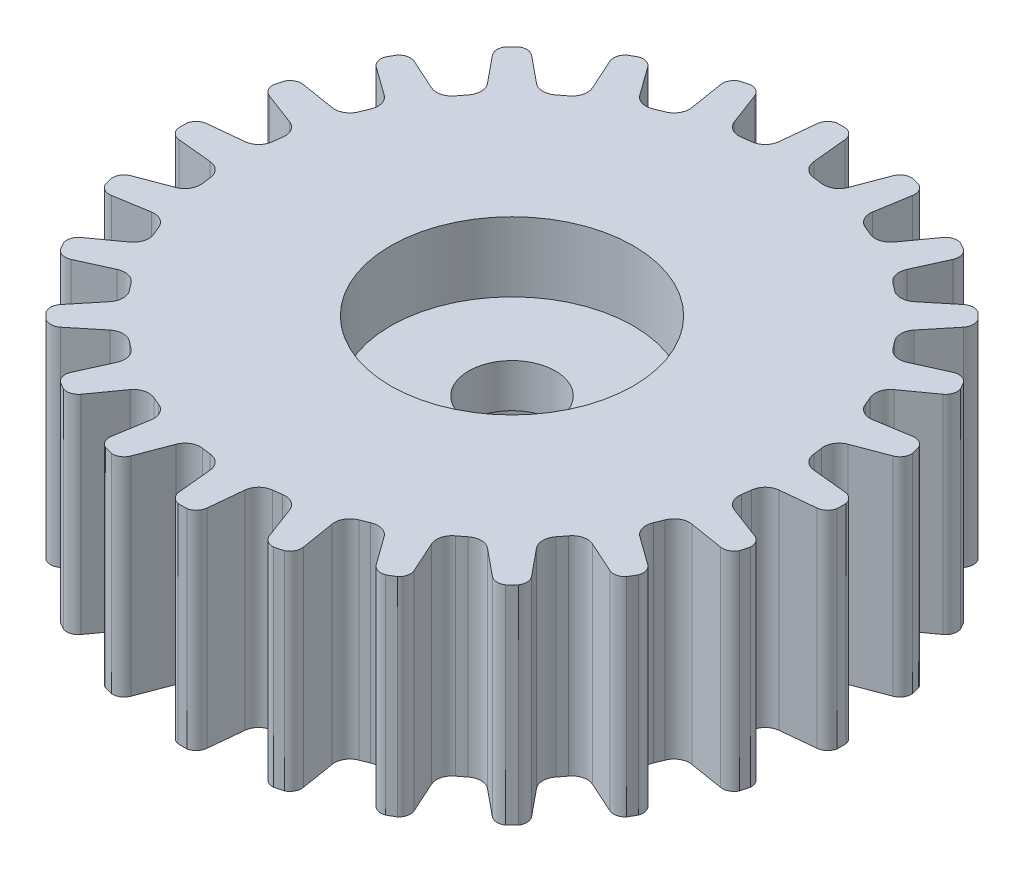
SolidWorks part; units mm, degrees
ref_plane "Front Plane" through (0, 0, 0) normal (0, 0, 1) x (1, 0, 0)
ref_plane "Top Plane" through (0, 0, 0) normal (0, 1, 0) x (1, 0, 0)
ref_plane "Right Plane" through (0, 0, 0) normal (1, 0, 0) x (0, 0, -1)
sketch "Sketch1" plane through (0, 0, 0) normal (0, 1, 0) x (1, 0, 0)
  circle A0 centre (0, 0) radius 2.45
  circle A1 centre (0, 0) radius 9.5
  dimension "D1" = 4.9
  dimension "D2" = 19
extrude "Boss-Extrude1" add sketch "Sketch1" along normal blind 6
sketch "Sketch2" plane through (0, 6, 0) normal (0, 1, 0) x (1, 0, 0)
  line L0 (0, 0) -> (0, 10.7871) construction
  line L1 (0.5, 8.2) -> (0.4, 9.2)
  line L2 (-0.5, 8.2) -> (-0.4, 9.2)
  line L3 (2.6053, 7.7912) -> (2.7675, 8.783)
  line L4 (1.6394, 8.05) -> (1.9948, 8.99)
  line L5 (4.533, 6.8514) -> (4.9464, 7.7674)
  line L6 (3.667, 7.3514) -> (4.2536, 8.1674)
  line L7 (6.1518, 5.4447) -> (6.7882, 6.2225)
  line L8 (5.4447, 6.1518) -> (6.2225, 6.7882)
  line L9 (7.3514, 3.667) -> (8.1674, 4.2536)
  line L10 (6.8514, 4.533) -> (7.7674, 4.9464)
  line L11 (8.05, 1.6394) -> (8.99, 1.9948)
  line L12 (7.7912, 2.6053) -> (8.783, 2.7675)
  line L13 (8.2, -0.5) -> (9.2, -0.4)
  line L14 (8.2, 0.5) -> (9.2, 0.4)
  line L15 (7.7912, -2.6053) -> (8.783, -2.7675)
  line L16 (8.05, -1.6394) -> (8.99, -1.9948)
  line L17 (6.8514, -4.533) -> (7.7674, -4.9464)
  line L18 (7.3514, -3.667) -> (8.1674, -4.2536)
  line L19 (5.4447, -6.1518) -> (6.2225, -6.7882)
  line L20 (6.1518, -5.4447) -> (6.7882, -6.2225)
  line L21 (3.667, -7.3514) -> (4.2536, -8.1674)
  line L22 (4.533, -6.8514) -> (4.9464, -7.7674)
  line L23 (1.6394, -8.05) -> (1.9948, -8.99)
  line L24 (2.6053, -7.7912) -> (2.7675, -8.783)
  line L25 (-0.5, -8.2) -> (-0.4, -9.2)
  line L26 (0.5, -8.2) -> (0.4, -9.2)
  line L27 (-2.6053, -7.7912) -> (-2.7675, -8.783)
  line L28 (-1.6394, -8.05) -> (-1.9948, -8.99)
  line L29 (-4.533, -6.8514) -> (-4.9464, -7.7674)
  line L30 (-3.667, -7.3514) -> (-4.2536, -8.1674)
  line L31 (-6.1518, -5.4447) -> (-6.7882, -6.2225)
  line L32 (-5.4447, -6.1518) -> (-6.2225, -6.7882)
  line L33 (-7.3514, -3.667) -> (-8.1674, -4.2536)
  line L34 (-6.8514, -4.533) -> (-7.7674, -4.9464)
  line L35 (-8.05, -1.6394) -> (-8.99, -1.9948)
  line L36 (-7.7912, -2.6053) -> (-8.783, -2.7675)
  line L37 (-8.2, 0.5) -> (-9.2, 0.4)
  line L38 (-8.2, -0.5) -> (-9.2, -0.4)
  line L39 (-7.7912, 2.6053) -> (-8.783, 2.7675)
  line L40 (-8.05, 1.6394) -> (-8.99, 1.9948)
  line L41 (-6.8514, 4.533) -> (-7.7674, 4.9464)
  line L42 (-7.3514, 3.667) -> (-8.1674, 4.2536)
  line L43 (-5.4447, 6.1518) -> (-6.2225, 6.7882)
  line L44 (-6.1518, 5.4447) -> (-6.7882, 6.2225)
  line L45 (-3.667, 7.3514) -> (-4.2536, 8.1674)
  line L46 (-4.533, 6.8514) -> (-4.9464, 7.7674)
  line L47 (-1.6394, 8.05) -> (-1.9948, 8.99)
  line L48 (-2.6053, 7.7912) -> (-2.7675, 8.783)
  arc A0 (2.8881, 7.3013) -> (3.1206, 7.205) centre (0, 0) cw
  arc A2 (0.9, 7.8) -> (1.1495, 7.7672) centre (0, 0) cw
  arc A3 (0.5, 8.2) -> (0.9, 7.8) centre (0.9444, 8.2444) ccw
  arc A4 (0, 9.5) -> (0.4, 9.2) centre (0.0622, 9.1662) cw
  arc A5 (-0.5, 8.2) -> (-0.9, 7.8) centre (-0.9444, 8.2444) cw
  arc A6 (0, 9.5) -> (-0.4, 9.2) centre (-0.0622, 9.1662) ccw
  arc A7 (2.6053, 7.7912) -> (2.8881, 7.3013) centre (3.0461, 7.7191) ccw
  arc A8 (2.4588, 9.1763) -> (2.7675, 8.783) centre (2.4324, 8.8378) cw
  arc A9 (1.6394, 8.05) -> (1.1495, 7.7672) centre (1.2216, 8.208) cw
  arc A10 (2.4588, 9.1763) -> (1.9948, 8.99) centre (2.3123, 8.87) ccw
  arc A11 (4.6794, 6.305) -> (4.879, 6.1518) centre (0, 0) cw
  arc A12 (4.533, 6.8514) -> (4.6794, 6.305) centre (4.9401, 6.6677) ccw
  arc A13 (4.75, 8.2272) -> (4.9464, 7.7674) centre (4.6369, 7.9071) cw
  arc A14 (3.667, 7.3514) -> (3.1206, 7.205) centre (3.3043, 7.6121) cw
  arc A15 (4.75, 8.2272) -> (4.2536, 8.1674) centre (4.5293, 7.9693) ccw
  arc A16 (6.1518, 4.879) -> (6.305, 4.6794) centre (0, 0) cw
  arc A17 (6.1518, 5.4447) -> (6.1518, 4.879) centre (6.4975, 5.1619) ccw
  arc A18 (6.7175, 6.7175) -> (6.7882, 6.2225) centre (6.5254, 6.4375) cw
  arc A19 (5.4447, 6.1518) -> (4.879, 6.1518) centre (5.1619, 6.4975) cw
  arc A20 (6.7175, 6.7175) -> (6.2225, 6.7882) centre (6.4375, 6.5254) ccw
  arc A21 (7.205, 3.1206) -> (7.3013, 2.8881) centre (0, 0) cw
  arc A22 (7.3514, 3.667) -> (7.205, 3.1206) centre (7.6121, 3.3043) ccw
  arc A23 (8.2272, 4.75) -> (8.1674, 4.2536) centre (7.9693, 4.5293) cw
  arc A24 (6.8514, 4.533) -> (6.305, 4.6794) centre (6.6677, 4.9401) cw
  arc A25 (8.2272, 4.75) -> (7.7674, 4.9464) centre (7.9071, 4.6369) ccw
  arc A26 (7.7672, 1.1495) -> (7.8, 0.9) centre (0, 0) cw
  arc A27 (8.05, 1.6394) -> (7.7672, 1.1495) centre (8.208, 1.2216) ccw
  arc A28 (9.1763, 2.4588) -> (8.99, 1.9948) centre (8.87, 2.3123) cw
  arc A29 (7.7912, 2.6053) -> (7.3013, 2.8881) centre (7.7191, 3.0461) cw
  arc A30 (9.1763, 2.4588) -> (8.783, 2.7675) centre (8.8378, 2.4324) ccw
  arc A31 (7.8, -0.9) -> (7.7672, -1.1495) centre (0, 0) cw
  arc A32 (8.2, -0.5) -> (7.8, -0.9) centre (8.2444, -0.9444) ccw
  arc A33 (9.5, 0) -> (9.2, -0.4) centre (9.1662, -0.0622) cw
  arc A34 (8.2, 0.5) -> (7.8, 0.9) centre (8.2444, 0.9444) cw
  arc A35 (9.5, 0) -> (9.2, 0.4) centre (9.1662, 0.0622) ccw
  arc A36 (7.3013, -2.8881) -> (7.205, -3.1206) centre (0, 0) cw
  arc A37 (7.7912, -2.6053) -> (7.3013, -2.8881) centre (7.7191, -3.0461) ccw
  arc A38 (9.1763, -2.4588) -> (8.783, -2.7675) centre (8.8378, -2.4324) cw
  arc A39 (8.05, -1.6394) -> (7.7672, -1.1495) centre (8.208, -1.2216) cw
  arc A40 (9.1763, -2.4588) -> (8.99, -1.9948) centre (8.87, -2.3123) ccw
  arc A41 (6.305, -4.6794) -> (6.1518, -4.879) centre (0, 0) cw
  arc A42 (6.8514, -4.533) -> (6.305, -4.6794) centre (6.6677, -4.9401) ccw
  arc A43 (8.2272, -4.75) -> (7.7674, -4.9464) centre (7.9071, -4.6369) cw
  arc A44 (7.3514, -3.667) -> (7.205, -3.1206) centre (7.6121, -3.3043) cw
  arc A45 (8.2272, -4.75) -> (8.1674, -4.2536) centre (7.9693, -4.5293) ccw
  arc A46 (4.879, -6.1518) -> (4.6794, -6.305) centre (0, 0) cw
  arc A47 (5.4447, -6.1518) -> (4.879, -6.1518) centre (5.1619, -6.4975) ccw
  arc A48 (6.7175, -6.7175) -> (6.2225, -6.7882) centre (6.4375, -6.5254) cw
  arc A49 (6.1518, -5.4447) -> (6.1518, -4.879) centre (6.4975, -5.1619) cw
  arc A50 (6.7175, -6.7175) -> (6.7882, -6.2225) centre (6.5254, -6.4375) ccw
  arc A51 (3.1206, -7.205) -> (2.8881, -7.3013) centre (0, 0) cw
  arc A52 (3.667, -7.3514) -> (3.1206, -7.205) centre (3.3043, -7.6121) ccw
  arc A53 (4.75, -8.2272) -> (4.2536, -8.1674) centre (4.5293, -7.9693) cw
  arc A54 (4.533, -6.8514) -> (4.6794, -6.305) centre (4.9401, -6.6677) cw
  arc A55 (4.75, -8.2272) -> (4.9464, -7.7674) centre (4.6369, -7.9071) ccw
  arc A56 (1.1495, -7.7672) -> (0.9, -7.8) centre (0, 0) cw
  arc A57 (1.6394, -8.05) -> (1.1495, -7.7672) centre (1.2216, -8.208) ccw
  arc A58 (2.4588, -9.1763) -> (1.9948, -8.99) centre (2.3123, -8.87) cw
  arc A59 (2.6053, -7.7912) -> (2.8881, -7.3013) centre (3.0461, -7.7191) cw
  arc A60 (2.4588, -9.1763) -> (2.7675, -8.783) centre (2.4324, -8.8378) ccw
  arc A61 (-0.9, -7.8) -> (-1.1495, -7.7672) centre (0, 0) cw
  arc A62 (-0.5, -8.2) -> (-0.9, -7.8) centre (-0.9444, -8.2444) ccw
  arc A63 (0, -9.5) -> (-0.4, -9.2) centre (-0.0622, -9.1662) cw
  arc A64 (0.5, -8.2) -> (0.9, -7.8) centre (0.9444, -8.2444) cw
  arc A65 (0, -9.5) -> (0.4, -9.2) centre (0.0622, -9.1662) ccw
  arc A66 (-2.8881, -7.3013) -> (-3.1206, -7.205) centre (0, 0) cw
  arc A67 (-2.6053, -7.7912) -> (-2.8881, -7.3013) centre (-3.0461, -7.7191) ccw
  arc A68 (-2.4588, -9.1763) -> (-2.7675, -8.783) centre (-2.4324, -8.8378) cw
  arc A69 (-1.6394, -8.05) -> (-1.1495, -7.7672) centre (-1.2216, -8.208) cw
  arc A70 (-2.4588, -9.1763) -> (-1.9948, -8.99) centre (-2.3123, -8.87) ccw
  arc A71 (-4.6794, -6.305) -> (-4.879, -6.1518) centre (0, 0) cw
  arc A72 (-4.533, -6.8514) -> (-4.6794, -6.305) centre (-4.9401, -6.6677) ccw
  arc A73 (-4.75, -8.2272) -> (-4.9464, -7.7674) centre (-4.6369, -7.9071) cw
  arc A74 (-3.667, -7.3514) -> (-3.1206, -7.205) centre (-3.3043, -7.6121) cw
  arc A75 (-4.75, -8.2272) -> (-4.2536, -8.1674) centre (-4.5293, -7.9693) ccw
  arc A76 (-6.1518, -4.879) -> (-6.305, -4.6794) centre (0, 0) cw
  arc A77 (-6.1518, -5.4447) -> (-6.1518, -4.879) centre (-6.4975, -5.1619) ccw
  arc A78 (-6.7175, -6.7175) -> (-6.7882, -6.2225) centre (-6.5254, -6.4375) cw
  arc A79 (-5.4447, -6.1518) -> (-4.879, -6.1518) centre (-5.1619, -6.4975) cw
  arc A80 (-6.7175, -6.7175) -> (-6.2225, -6.7882) centre (-6.4375, -6.5254) ccw
  arc A81 (-7.205, -3.1206) -> (-7.3013, -2.8881) centre (0, 0) cw
  arc A82 (-7.3514, -3.667) -> (-7.205, -3.1206) centre (-7.6121, -3.3043) ccw
  arc A83 (-8.2272, -4.75) -> (-8.1674, -4.2536) centre (-7.9693, -4.5293) cw
  arc A84 (-6.8514, -4.533) -> (-6.305, -4.6794) centre (-6.6677, -4.9401) cw
  arc A85 (-8.2272, -4.75) -> (-7.7674, -4.9464) centre (-7.9071, -4.6369) ccw
  arc A86 (-7.7672, -1.1495) -> (-7.8, -0.9) centre (0, 0) cw
  arc A87 (-8.05, -1.6394) -> (-7.7672, -1.1495) centre (-8.208, -1.2216) ccw
  arc A88 (-9.1763, -2.4588) -> (-8.99, -1.9948) centre (-8.87, -2.3123) cw
  arc A89 (-7.7912, -2.6053) -> (-7.3013, -2.8881) centre (-7.7191, -3.0461) cw
  arc A90 (-9.1763, -2.4588) -> (-8.783, -2.7675) centre (-8.8378, -2.4324) ccw
  arc A91 (-7.8, 0.9) -> (-7.7672, 1.1495) centre (0, 0) cw
  arc A92 (-8.2, 0.5) -> (-7.8, 0.9) centre (-8.2444, 0.9444) ccw
  arc A93 (-9.5, 0) -> (-9.2, 0.4) centre (-9.1662, 0.0622) cw
  arc A94 (-8.2, -0.5) -> (-7.8, -0.9) centre (-8.2444, -0.9444) cw
  arc A95 (-9.5, 0) -> (-9.2, -0.4) centre (-9.1662, -0.0622) ccw
  arc A96 (-7.3013, 2.8881) -> (-7.205, 3.1206) centre (0, 0) cw
  arc A97 (-7.7912, 2.6053) -> (-7.3013, 2.8881) centre (-7.7191, 3.0461) ccw
  arc A98 (-9.1763, 2.4588) -> (-8.783, 2.7675) centre (-8.8378, 2.4324) cw
  arc A99 (-8.05, 1.6394) -> (-7.7672, 1.1495) centre (-8.208, 1.2216) cw
  arc A100 (-9.1763, 2.4588) -> (-8.99, 1.9948) centre (-8.87, 2.3123) ccw
  arc A101 (-6.305, 4.6794) -> (-6.1518, 4.879) centre (0, 0) cw
  arc A102 (-6.8514, 4.533) -> (-6.305, 4.6794) centre (-6.6677, 4.9401) ccw
  arc A103 (-8.2272, 4.75) -> (-7.7674, 4.9464) centre (-7.9071, 4.6369) cw
  arc A104 (-7.3514, 3.667) -> (-7.205, 3.1206) centre (-7.6121, 3.3043) cw
  arc A105 (-8.2272, 4.75) -> (-8.1674, 4.2536) centre (-7.9693, 4.5293) ccw
  arc A106 (-4.879, 6.1518) -> (-4.6794, 6.305) centre (0, 0) cw
  arc A107 (-5.4447, 6.1518) -> (-4.879, 6.1518) centre (-5.1619, 6.4975) ccw
  arc A108 (-6.7175, 6.7175) -> (-6.2225, 6.7882) centre (-6.4375, 6.5254) cw
  arc A109 (-6.1518, 5.4447) -> (-6.1518, 4.879) centre (-6.4975, 5.1619) cw
  arc A110 (-6.7175, 6.7175) -> (-6.7882, 6.2225) centre (-6.5254, 6.4375) ccw
  arc A111 (-3.1206, 7.205) -> (-2.8881, 7.3013) centre (0, 0) cw
  arc A112 (-3.667, 7.3514) -> (-3.1206, 7.205) centre (-3.3043, 7.6121) ccw
  arc A113 (-4.75, 8.2272) -> (-4.2536, 8.1674) centre (-4.5293, 7.9693) cw
  arc A114 (-4.533, 6.8514) -> (-4.6794, 6.305) centre (-4.9401, 6.6677) cw
  arc A115 (-4.75, 8.2272) -> (-4.9464, 7.7674) centre (-4.6369, 7.9071) ccw
  arc A116 (-1.1495, 7.7672) -> (-0.9, 7.8) centre (0, 0) cw
  arc A117 (-1.6394, 8.05) -> (-1.1495, 7.7672) centre (-1.2216, 8.208) ccw
  arc A118 (-2.4588, 9.1763) -> (-1.9948, 8.99) centre (-2.3123, 8.87) cw
  arc A119 (-2.6053, 7.7912) -> (-2.8881, 7.3013) centre (-3.0461, 7.7191) cw
  arc A120 (-2.4588, 9.1763) -> (-2.7675, 8.783) centre (-2.4324, 8.8378) ccw
  circle A121 centre (0, 0) radius 9.5 construction
  circle A132 centre (0, 0) radius 11.1781
  point P296 (0, 0)
  dimension "D7" = 24
  dimension "D1" = 0.4
  dimension "D2" = 0.1
  dimension "D3" = 1
  dimension "D4" = 0.3
  dimension "D5" = 0.4
  dimension "D6" = 0.4
extrude "Cut-Extrude1" cut sketch "Sketch2" against normal up to next
sketch "Sketch3" plane through (0, 6, 0) normal (0, 1, 0) x (1, 0, 0)
  circle A0 centre (0, 0) radius 2.45 construction
  circle A1 centre (0, 0) radius 2.45
  circle A2 centre (0, 0) radius 1.25
  dimension "D1" = 2.5
extrude "Boss-Extrude2" add sketch "Sketch3" against normal blind 3.25
sketch "Sketch4" plane through (0, 6, 0) normal (0, 1, 0) x (1, 0, 0)
  circle A0 centre (0, 0) radius 3.5
  dimension "D1" = 7
extrude "Cut-Extrude2" cut sketch "Sketch4" against normal blind 2
